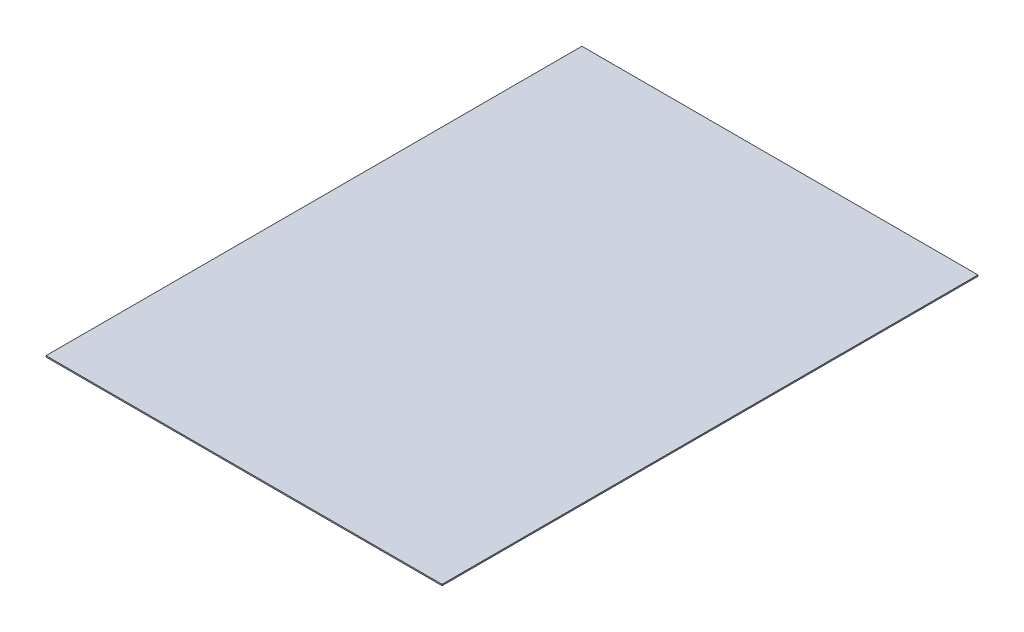
SolidWorks part; units mm, degrees
material "ABS"
ref_plane "Front Plane" through (0, 0, 0) normal (0, 0, 1) x (1, 0, 0)
ref_plane "Top Plane" through (0, 0, 0) normal (0, 1, 0) x (1, 0, 0)
ref_plane "Right Plane" through (0, 0, 0) normal (1, 0, 0) x (0, 0, -1)
sketch "Sketch1" plane through (0, 0, 0) normal (0, 1, 0) x (1, 0, 0)
  line L1 (-85, 115) -> (85, 115)
  line L2 (-85, 115) -> (-85, -115)
  line L3 (-85, -115) -> (85, -115)
  line L4 (85, 115) -> (85, -115)
  line L5 (-85, 115) -> (85, -115) construction
  line L6 (-85, -115) -> (85, 115) construction
  point P0 (0, 0)
  dimension "D1" = 170
  dimension "D2" = 230
extrude "Boss-Extrude1" add sketch "Sketch1" along normal up to surface (0.535 mm away)
